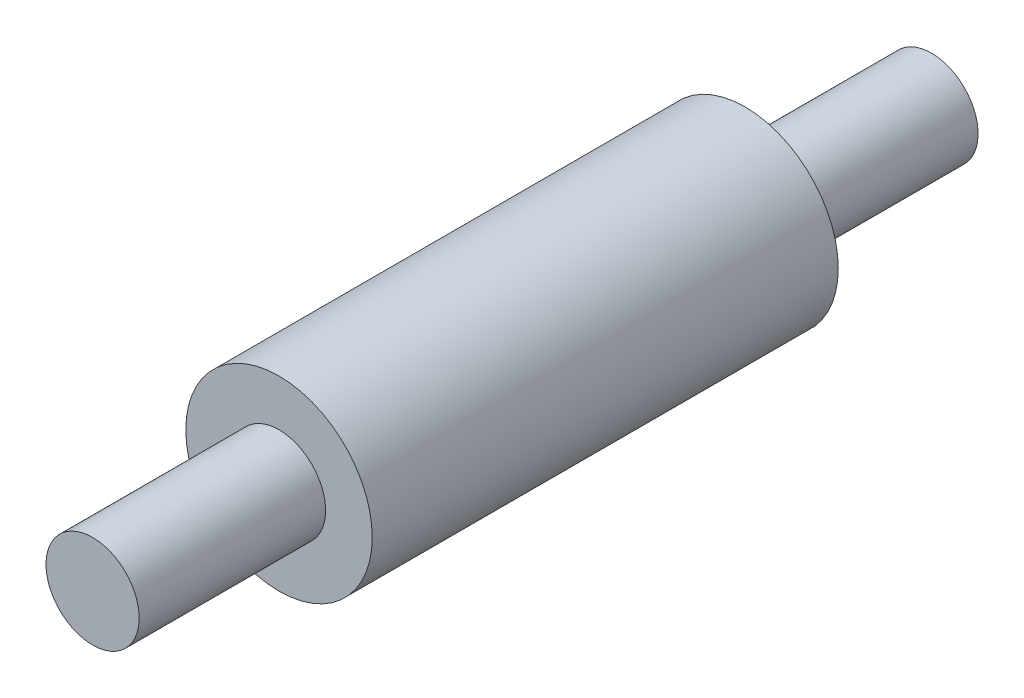
SolidWorks part; units mm, degrees
material "1060 Alloy"
ref_plane "Front Plane" through (0, 0, 0) normal (0, 0, 1) x (1, 0, 0)
ref_plane "Top Plane" through (0, 0, 0) normal (0, 1, 0) x (1, 0, 0)
ref_plane "Right Plane" through (0, 0, 0) normal (1, 0, 0) x (0, 0, -1)
sketch "Sketch1" plane through (0, 0, 0) normal (0, 0, 1) x (1, 0, 0)
  circle A0 centre (0, 0) radius 6.35
  dimension "D1" = 12.7
extrude "Boss-Extrude1" add sketch "Sketch1" along normal blind 57.15
ref_plane "Plane1" through (0, 0, 28.575) normal (0, 0, 1) x (1, 0, 0)
sketch "Sketch3" plane through (0, 0, 0) normal (0, 0, -1) x (-1, 0, 0)
  circle A0 centre (0, 0) radius 6.35
  circle A1 centre (0, 0) radius 3.175
  dimension "D1" = 6.35
extrude "Cut-Extrude1" cut sketch "Sketch3" against normal blind 12.7
mirror "Mirror1" about plane through (0, 0, 28.575) normal (0, 0, 1) of "Cut-Extrude1"
